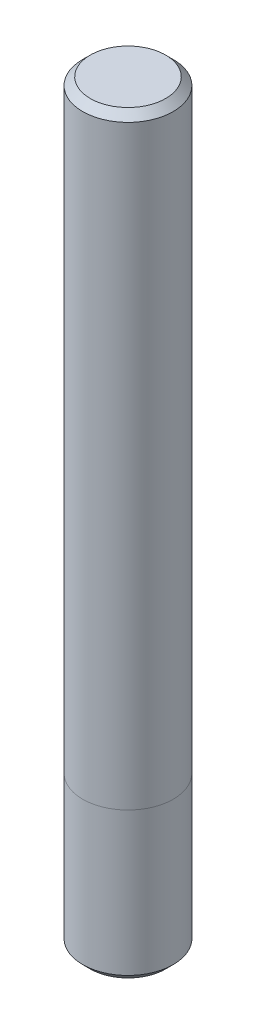
SolidWorks part; units mm, degrees
ref_plane "Front Plane" through (0, 0, 0) normal (0, 0, 1) x (1, 0, 0)
ref_plane "Top Plane" through (0, 0, 0) normal (0, 1, 0) x (1, 0, 0)
ref_plane "Right Plane" through (0, 0, 0) normal (1, 0, 0) x (0, 0, -1)
sketch "Sketch1" plane through (0, 0, 0) normal (0, 1, 0) x (1, 0, 0)
  circle A0 centre (0, 0) radius 1.5
  dimension "D1" = 3
extrude "Boss-Extrude1" add sketch "Sketch1" along normal mid plane 25
chamfer "Chamfer1" distance 0.25 angle 45 2 edges at (0, -12.5, 1.5) (0, 12.5, 1.5)
sketch "Sketch2" plane through (0, 0, 0) normal (0, 0, 1) x (1, 0, 0)
  line L0 (-1.5, -7.5) -> (1.5, -7.5)
  line L1 (-1.5, 12.25) -> (-1.5, -12.25) construction
  line L2 (1.5, -12.25) -> (1.5, 12.25) construction
  line L3 (-1.25, -12.5) -> (1.25, -12.5) construction
  dimension "D1" = 5
split line "Split Line1"
